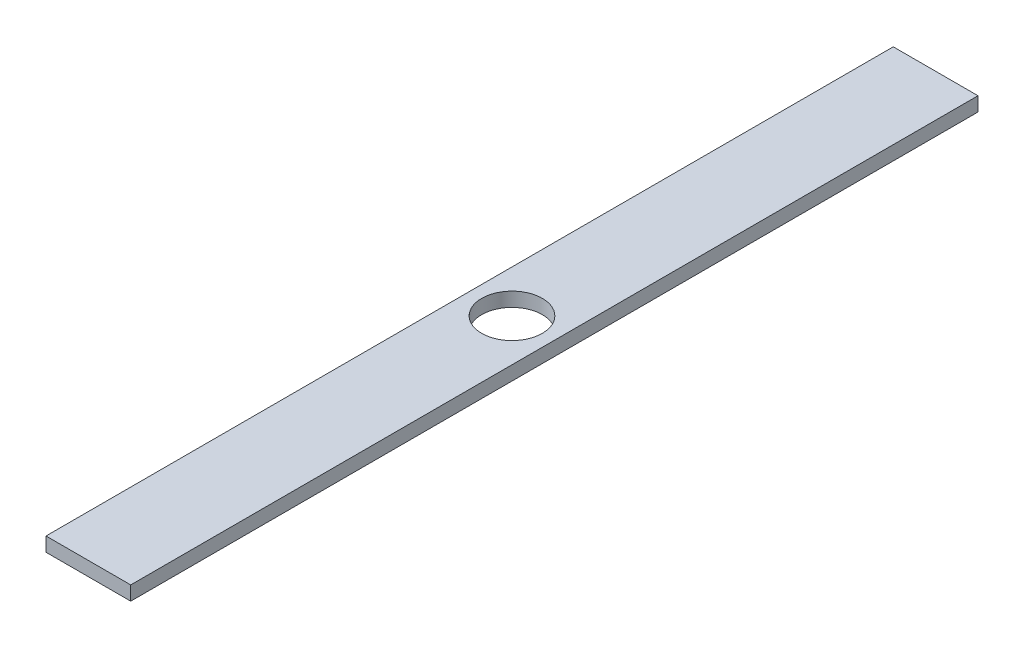
SolidWorks part; units mm, degrees
material "Pine"
ref_plane "Front Plane" through (0, 0, 0) normal (0, 0, 1) x (1, 0, 0)
ref_plane "Top Plane" through (0, 0, 0) normal (0, 1, 0) x (1, 0, 0)
ref_plane "Right Plane" through (0, 0, 0) normal (1, 0, 0) x (0, 0, -1)
sketch "Sketch1" plane through (0, 0, 0) normal (0, 1, 0) x (1, 0, 0)
  line L1 (-19.05, -190.5) -> (19.05, -190.5)
  line L2 (-19.05, -190.5) -> (-19.05, 190.5)
  line L3 (-19.05, 190.5) -> (19.05, 190.5)
  line L4 (19.05, -190.5) -> (19.05, 190.5)
  line L5 (-19.05, -190.5) -> (19.05, 190.5) construction
  line L6 (-19.05, 190.5) -> (19.05, -190.5) construction
  circle A0 centre (0, 0) radius 13.6319
  point P0 (0, 0)
  dimension "D1" = 38.1
  dimension "D2" = 381
extrude "Boss-Extrude1" add sketch "Sketch1" along normal blind 6.35
